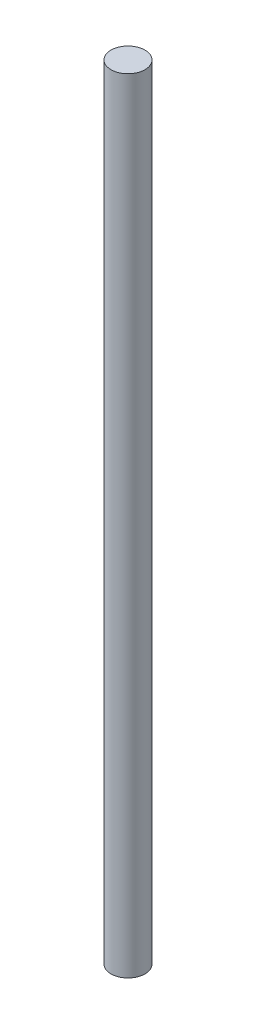
SolidWorks part; units mm, degrees
ref_plane "Front Plane" through (0, 0, 0) normal (0, 0, 1) x (1, 0, 0)
ref_plane "Top Plane" through (0, 0, 0) normal (0, 1, 0) x (1, 0, 0)
ref_plane "Right Plane" through (0, 0, 0) normal (1, 0, 0) x (0, 0, -1)
sketch "Sketch1" plane through (0, 0, 0) normal (0, 1, 0) x (1, 0, 0)
  circle A0 centre (0, 0) radius 1.378
  dimension "D1" = 2.7559
extrude "Boss-Extrude1" add sketch "Sketch1" along normal blind 63.5
